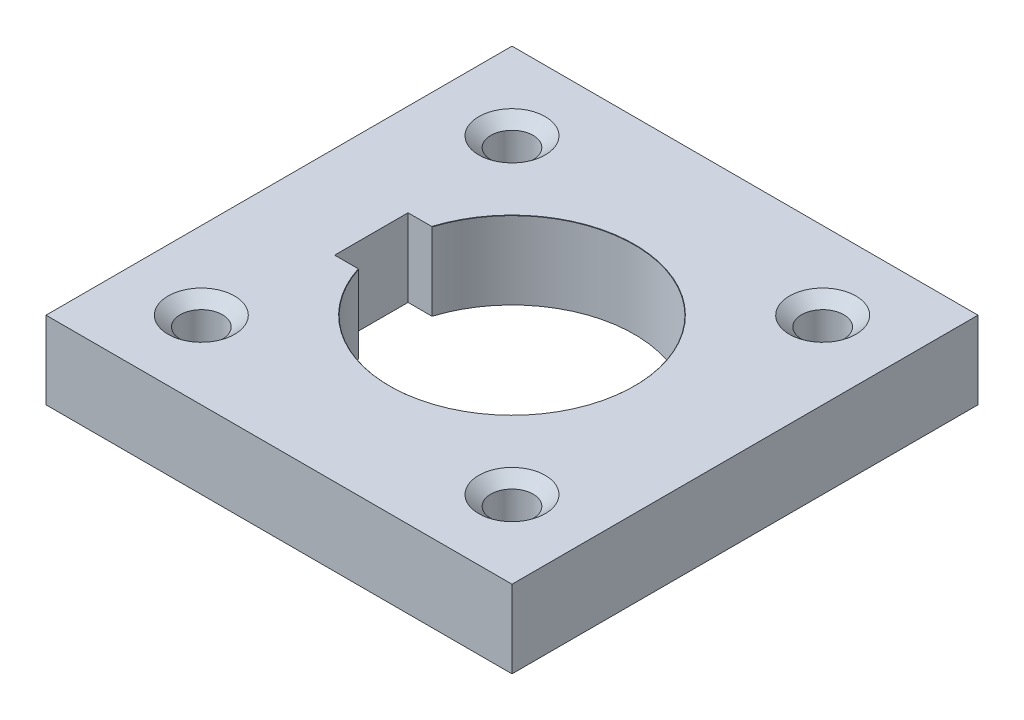
SolidWorks part; units mm, degrees
material "6061 Alloy"
ref_plane "Front" through (0, 0, 0) normal (0, 0, 1) x (1, 0, 0)
ref_plane "Top" through (0, 0, 0) normal (0, 1, 0) x (1, 0, 0)
ref_plane "Right" through (0, 0, 0) normal (1, 0, 0) x (0, 0, -1)
sketch "Sketch1" plane through (0, 0, 0) normal (0, 1, 0) x (1, 0, 0)
  line L1 (0, 0) -> (38.1, 0)
  line L2 (0, 0) -> (0, 38.1)
  line L3 (0, 38.1) -> (38.1, 38.1)
  line L4 (38.1, 0) -> (38.1, 38.1)
  dimension "D1" = 38.1
extrude "Boss-Extrude1" add sketch "Sketch1" along normal blind 6.35
hole_wizard "#8-32 Tapped Hole1" positions "Sketch2" profile "Sketch3" tap size "#8-32" standard "ANSI Inch" end condition through all
sketch "Sketch2" plane through (0, 6.35, 0) normal (0, 1, 0) x (1, 0, 0)
  line L0 (38.1, 6.35) -> (31.75, 6.35) construction
  line L1 (38.1, 0) -> (38.1, 38.1) construction
  line L2 (31.75, 6.35) -> (31.75, 0) construction
  line L3 (-50, 0) -> (50, 0) construction
  line L5 (0, 6.35) -> (6.35, 6.35) construction
  line L6 (0, -50) -> (0, 50) construction
  line L7 (6.35, 6.35) -> (6.35, 0) construction
  line L9 (0, 31.75) -> (6.35, 31.75) construction
  line L10 (6.35, 31.75) -> (6.35, 38.1) construction
  line L11 (38.1, 38.1) -> (0, 38.1) construction
  line L13 (31.75, 38.1) -> (31.75, 31.75) construction
  line L14 (31.75, 31.75) -> (38.1, 31.75) construction
  point P0 (31.75, 31.75)
  point P2 (6.35, 31.75)
  point P4 (6.35, 6.35)
  point P6 (31.75, 6.35)
  dimension "D1" = 6.35
sketch "Sketch3" plane through (31.75, 6.35, -31.75) normal (1, 0, 0) x (0, 0, 1)
  line L0 (0, 0) -> (0, 6.35)
  line L1 (0, 6.35) -> (1.7272, 6.35)
  line L2 (1.7272, 6.35) -> (1.7272, 0.8312)
  line L3 (1.7272, 0.8312) -> (2.7178, 0)
  line L5 (2.7178, 0) -> (0, 0)
  line L6 (-1.7272, 0.8312) -> (-2.7178, 0) construction
  line L11 (0, -6.35) -> (0, 107.95) construction
  dimension "Thru Tap Drill Dia." = 3.4544
  dimension "Thru Tap Drill Depth" = 6.35
  dimension "Near C'Sink Dia." = 5.4356
  dimension "Near C'Sink Angle" = 100
cosmetic thread "Hole Thread1" parameters "D2"=4.1656
cosmetic thread "Hole Thread2" parameters "D2"=4.1656
cosmetic thread "Hole Thread3" parameters "D2"=4.1656
cosmetic thread "Hole Thread4" parameters "D2"=4.1656
hole_wizard "M18 Clearance Hole1" positions "Sketch4" profile "Sketch5" hole size "M18" standard "ANSI Metric" end condition through all
sketch "Sketch4" plane through (0, 6.35, 0) normal (0, 1, 0) x (1, 0, 0)
  line L0 (19.05, 38.1) -> (19.05, 0) construction
  line L1 (38.1, 38.1) -> (0, 38.1) construction
  line L2 (-50, 0) -> (50, 0) construction
  point P0 (19.05, 19.05)
  point P11 (0, 0)
sketch "Sketch5" plane through (19.05, 6.35, -19.05) normal (1, 0, 0) x (0, 0, 1)
  line L0 (0, 0) -> (0, 6.35)
  line L1 (0, 6.35) -> (10, 6.35)
  line L2 (10, 6.35) -> (10, 0.021)
  line L3 (10, 0.021) -> (10.025, 0)
  line L5 (10.025, 0) -> (0, 0)
  line L6 (-10, 0.021) -> (-10.025, 0) construction
  line L11 (0, -6.35) -> (0, 107.95) construction
  dimension "Thru Hole Dia." = 20
  dimension "Thru Hole Depth" = 6.35
  dimension "Near C'Sink Dia." = 20.05
  dimension "Near C'Sink Angle" = 100
sketch "Sketch6" plane through (0, 6.35, 0) normal (0, 1, 0) x (1, 0, 0)
  line L0 (28.05, 38.1) -> (28.05, 0) construction
  line L1 (7.55, 16.05) -> (13.55, 16.05)
  line L2 (7.55, 16.05) -> (7.55, 22.05)
  line L3 (7.55, 22.05) -> (13.55, 22.05)
  line L4 (13.55, 16.05) -> (13.55, 22.05)
  line L7 (7.55, 19.05) -> (0, 19.05) construction
  line L8 (0, -50) -> (0, 50) construction
  line L9 (0, 38.1) -> (0, 0) construction
  line L10 (38.1, 38.1) -> (0, 38.1) construction
  line L11 (-50, 0) -> (50, 0) construction
  circle A0 centre (19.05, 19.05) radius 9 construction
  circle A2 centre (19.05, 19.05) radius 10.025 construction
  dimension "D2" = 18
  dimension "D1" = 6
  dimension "D3" = 14.5
  dimension "D4" = 20.5
extrude "Cut-Extrude1" cut sketch "Sketch6" against normal through all
